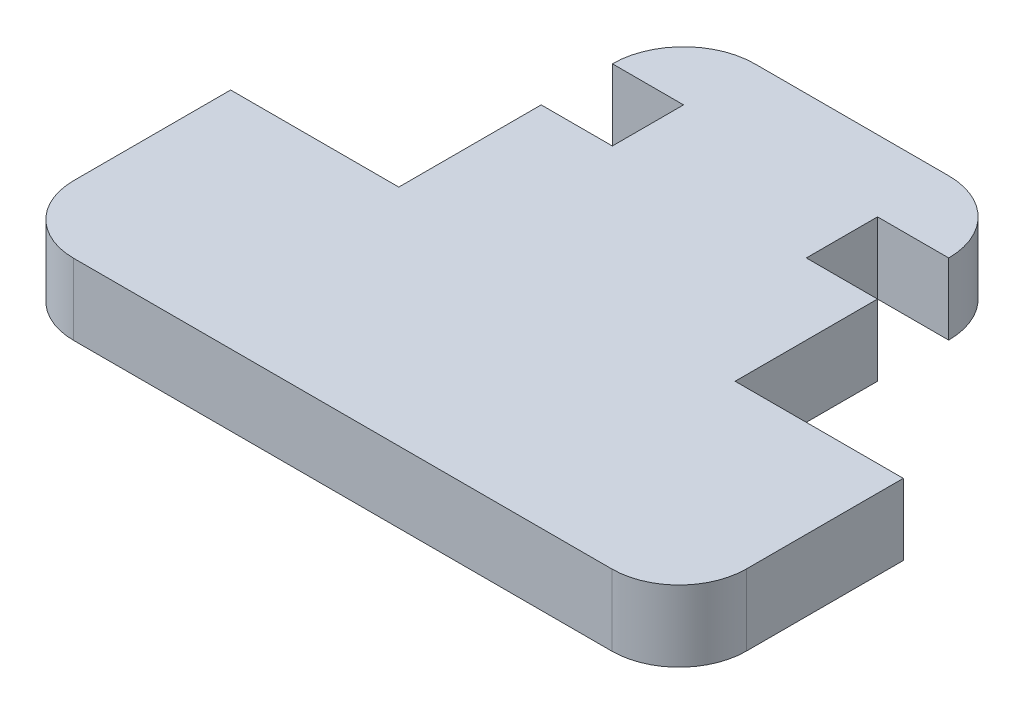
SolidWorks part; units mm, degrees
ref_plane "Front Plane" through (0, 0, 0) normal (0, 0, 1) x (1, 0, 0)
ref_plane "Top Plane" through (0, 0, 0) normal (0, 1, 0) x (1, 0, 0)
ref_plane "Right Plane" through (0, 0, 0) normal (1, 0, 0) x (0, 0, -1)
sketch "Sketch1" plane through (0, 0, 0) normal (0, 1, 0) x (1, 0, 0)
  line L0 (-15, 0) -> (15, 0)
  line L3 (-15, -10) -> (15, -10)
  line L4 (15, 0) -> (15, -10)
  line L5 (7.5, 6.35) -> (7.5, 3.175)
  line L6 (-7.5, 3.175) -> (-7.5, 6.35)
  line L7 (-4.325, 6.35) -> (-4.325, 9.525)
  line L8 (-4.325, 9.525) -> (-7.5, 9.525)
  line L9 (-4.325, 9.525) -> (4.325, 9.525)
  line L10 (-7.5, 6.35) -> (7.5, 6.35)
  line L11 (-7.5, 0) -> (7.5, 0)
  line L12 (7.5, 0) -> (7.5, 3.175)
  line L13 (-7.5, 0) -> (-7.5, 3.175)
  line L18 (4.325, 6.35) -> (7.5, 6.35)
  line L19 (-4.325, 6.35) -> (-7.5, 6.35)
  line L20 (4.325, 9.525) -> (4.325, 6.35)
  line L21 (-7.5, 6.35) -> (-3.85, 6.35)
  line L22 (4.325, 9.525) -> (7.5, 9.525)
  line L24 (-15, 0) -> (-15, -10)
  line L25 (-4.325, 12.7) -> (4.325, 12.7)
  arc A0 (7.5, 9.525) -> (4.325, 12.7) centre (4.325, 9.525) ccw
  arc A1 (-7.5, 9.525) -> (-4.325, 12.7) centre (-4.325, 9.525) cw
  point P0 (0, 0)
  point P15 (0, 0)
  dimension "D1" = 3.175
  dimension "D2" = 30
  dimension "D5" = 15
extrude "Boss-Extrude2" add sketch "Sketch1" along normal blind 3.175 contours L0 L24 L3 L4 | L13 L0 L12 L5 L10 L6 | L20 L9 L7 L10 | A1 L8 L9 L22 A0 L25
fillet "Fillet3" radius 3 2 edges at (15, 1.5875, 10) (-15, 1.5875, 10)
